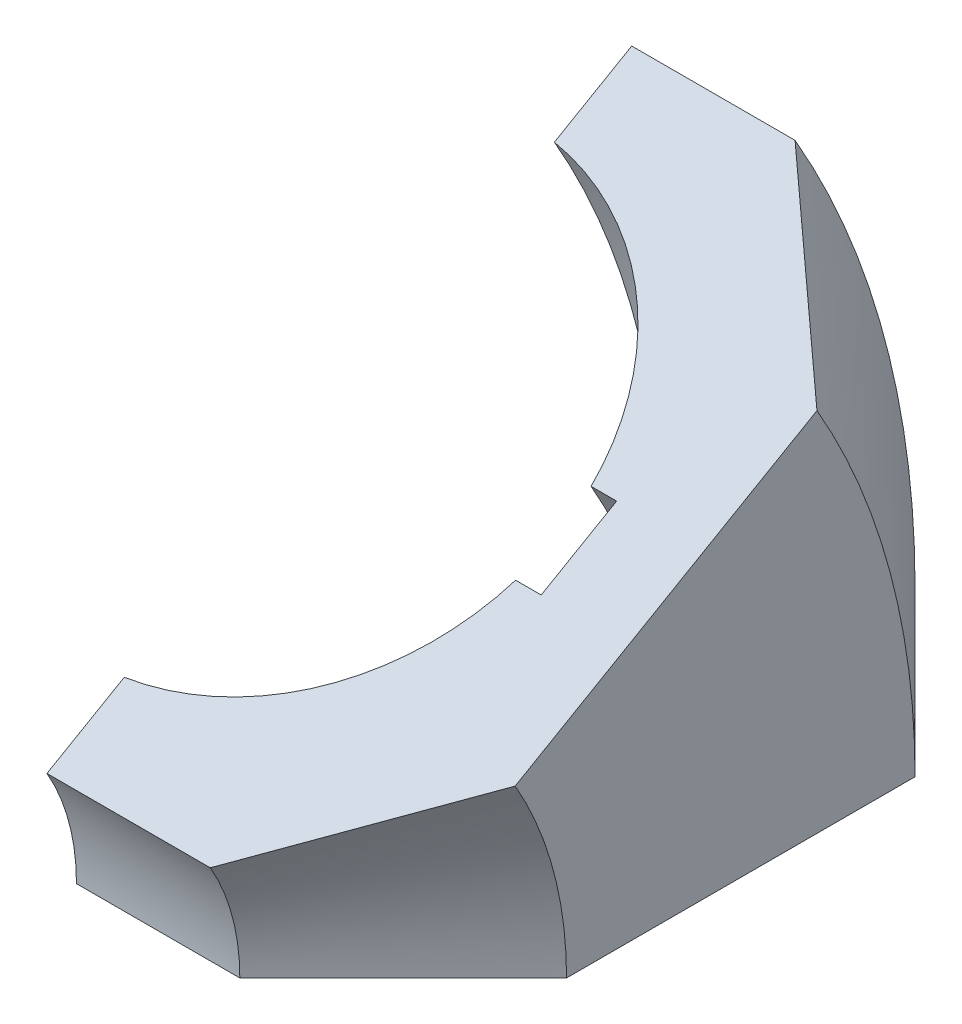
SolidWorks part; units mm, degrees
ref_plane "Front Plane" through (0, 0, 0) normal (0, 0, 1) x (1, 0, 0)
ref_plane "Top Plane" through (0, 0, 0) normal (0, 1, 0) x (1, 0, 0)
ref_plane "Right Plane" through (0, 0, 0) normal (1, 0, 0) x (0, 0, -1)
sketch "Sketch1" plane through (0, 0, 0) normal (1, 0, 0) x (0, 0, -1)
  line L0 (0, -32.3349) -> (0, 0) construction
  line L1 (0, 140) -> (0, 0) construction
  line L2 (0, 140) -> (68.7271, 140) construction
  line L3 (-6.8653, 25.6218) -> (-51.2436, 0) construction
  line L4 (55, 0) -> (-55, 0) construction
  line L5 (-6.8653, 25.6218) -> (-27.8209, 61.9178) construction
  arc A0 (0, 0) -> (-25.6218, 44.3782) centre (-51.2436, 0) ccw construction
  arc A1 (-25.6218, 44.3782) -> (0, 140) centre (0, 88.7564) cw construction
  arc A2 (0, 0) -> (-6.8653, 25.6218) centre (-51.2436, 0) ccw construction
  arc A3 (-6.8653, 25.6218) -> (0, 0) centre (-51.2436, 0) cw
  dimension "D1" = 140
  dimension "D2" = 30
sketch "Sketch2" plane through (0, 0, 0) normal (0, 1, 0) x (1, 0, 0)
  line L0 (0, 0) -> (0, 68.7271) construction
  line L1 (3, 31) -> (33, 31) construction
  line L2 (3, 31) -> (3, -31) construction
  line L3 (3, -31) -> (33, -31) construction
  line L4 (33, 31) -> (33, -31) construction
  line L5 (-55, 0) -> (55, 0) construction
  line L6 (23, -4) -> (25, -4) construction
  line L7 (23, -4) -> (23, 4) construction
  line L8 (23, 4) -> (25, 4) construction
  line L9 (25, -4) -> (25, 4) construction
  line L10 (23, -4) -> (25, 4) construction
  line L11 (23, 4) -> (25, -4) construction
  line L12 (23, 4) -> (22.6495, 4) construction
  line L13 (23, -4) -> (22.6495, -4) construction
  line L14 (3, 22.8035) -> (3, 31)
  line L15 (3, 31) -> (33, 31)
  line L16 (33, 31) -> (33, -31)
  line L17 (33, -31) -> (3, -31)
  line L18 (3, -31) -> (3, -22.8035)
  line L19 (22.6495, -4) -> (25, -4)
  line L20 (25, 4) -> (22.6495, 4)
  line L21 (25, 4) -> (25, -4)
  circle A0 centre (0, 0) radius 23 construction
  arc A1 (3, 22.8035) -> (22.6495, 4) centre (0, 0) cw
  arc A2 (22.6495, -4) -> (3, -22.8035) centre (0, 0) cw
  point P10 (24, 0)
  dimension "D1" = 46
  dimension "D2" = 3
  dimension "D3" = 2
  dimension "D4" = 8
  dimension "D5" = 31
  dimension "D6" = 31
  dimension "D7" = 30
sweep "Sweep3" add profiles "Sketch2" path "Sketch1"
chamfer "Chamfer1" distance 15 angle 45 2 edges at (33, 5.2394, 31.6898) (33, 21.2862, -28.1976)
